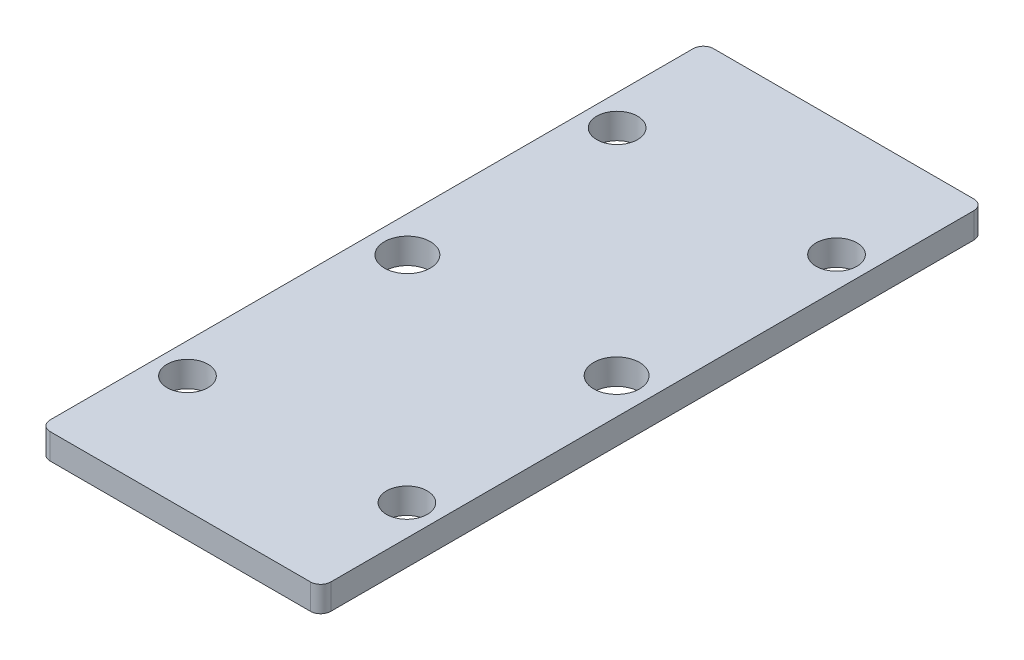
SolidWorks part; units mm, degrees
ref_plane "Alzado" through (0, 0, 0) normal (0, 0, 1) x (1, 0, 0)
ref_plane "Planta" through (0, 0, 0) normal (0, 1, 0) x (1, 0, 0)
ref_plane "Vista lateral" through (0, 0, 0) normal (1, 0, 0) x (0, 0, -1)
sketch "Croquis1" plane through (0, 0, 0) normal (0, 1, 0) x (1, 0, 0)
  line L0 (-27.5, 0) -> (27.5, 0) construction
  line L2 (-27.5, -63) -> (-27.5, 63)
  line L3 (-25.5, 65) -> (25.5, 65)
  line L4 (27.5, 63) -> (27.5, -63)
  line L5 (0, 65) -> (0, -65) construction
  line L7 (-25.5, -65) -> (25.5, -65)
  arc A0 (25.5, -65) -> (27.5, -63) centre (25.5, -63) ccw
  arc A1 (25.5, 65) -> (27.5, 63) centre (25.5, 63) cw
  arc A2 (-25.5, -65) -> (-27.5, -63) centre (-25.5, -63) cw
  arc A3 (-27.5, 63) -> (-25.5, 65) centre (-25.5, 63) cw
  point P11 (27.5, -65)
  point P16 (-27.5, -65)
  point P19 (-27.5, 65)
  dimension "D3" = 2
  dimension "D1" = 55
  dimension "D2" = 130
extrude "Saliente-Extruir1" add sketch "Croquis1" along normal blind 5
sketch "Croquis2" plane through (0, 5, 0) normal (0, 1, 0) x (1, 0, 0)
  line L0 (-27.5, 0) -> (27.5, 0) construction
  line L1 (-27.5, 63) -> (-27.5, -63) construction
  line L3 (0, -65) -> (0, 65) construction
  line L4 (-25.5, -65) -> (25.5, -65) construction
  line L5 (25.5, 65) -> (-25.5, 65) construction
  line L6 (27.5, -63) -> (27.5, 63) construction
  circle A0 centre (-20.5, 0) radius 4.5
  circle A1 centre (20.5, 0) radius 4.5
  circle A4 centre (-21.5, 42.1) radius 4
  circle A5 centre (-21.5, -42.1) radius 4
  circle A6 centre (21.5, 42.1) radius 4
  circle A7 centre (21.5, -42.1) radius 4
  dimension "D2" = 9
  dimension "D5" = 8
  dimension "D1" = 7
  dimension "D4" = 6
  dimension "D6" = 84.2
extrude "Cortar-Extruir1" cut sketch "Croquis2" against normal blind 10
